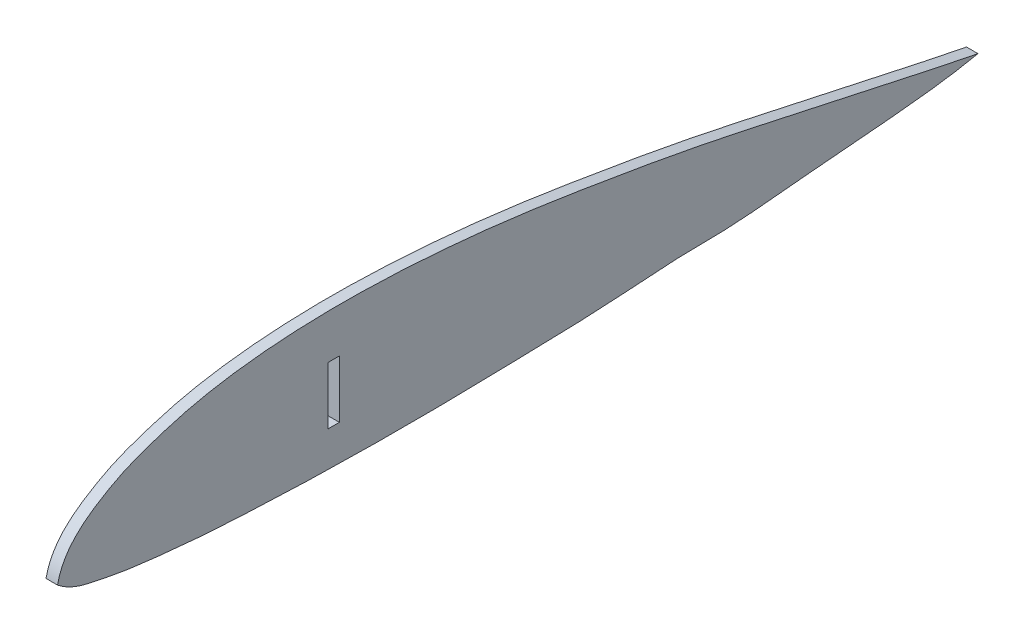
SolidWorks part; units mm, degrees
ref_plane "Спереди" through (0, 0, 0) normal (0, 0, 1) x (1, 0, 0)
ref_plane "Сверху" through (0, 0, 0) normal (0, 1, 0) x (1, 0, 0)
ref_plane "Справа" through (0, 0, 0) normal (1, 0, 0) x (0, 0, -1)
sketch "Эскиз1" plane through (0, 0, 0) normal (1, 0, 0) x (0, 0, -1)
  spline S0 degree 3 poles (-240, 0) (-238.5396, 6.886) (-231.612, 12.3378) (-222.1753, 17.4121) (-214.1119, 20.3435) (-204.1561, 23.2639) (-188.1046, 25.8933) (-168.0072, 26.9601) (-143.9456, 26.0264) (-119.9183, 23.5678) (-95.9538, 19.7588) (-71.9127, 15.562) (-48.006, 10.2206) (-23.9898, 5.1714) (-8.0375, 1.5236) (0, 0) knots 0 0 0 0 0.075346 0.102328 0.12789 0.177564 0.226025 0.321727 0.4173 0.513305 0.60992 0.706974 0.804635 0.902346 1 1 1 1
  spline S1 degree 3 poles (-240, 0) (-236.5239, -2.8866) (-230.2208, -4.0678) (-222.0286, -5.6488) (-214.0096, -6.6085) (-204.0195, -7.6506) (-188.0105, -8.621) (-168.0084, -9.355) (-143.9974, -9.5447) (-119.9964, -9.0006) (-95.9841, -8.4523) (-79.4445, -6.8615) (-63.4129, -6.9414) (-47.4215, -5.1493) (-23.952, -3.3462) (-7.916, -1.6722) (0, 0) knots 0 0 0 0 0.053475 0.078709 0.103753 0.153673 0.203448 0.302856 0.402199 0.501554 0.600955 0.70043 0.70748 0.799996 0.899716 1 1 1 1
  point P0 (-240, 0)
  point P1 (-234, 9.888)
  point P2 (-228, 14.16)
  point P3 (-222, 17.316)
  point P4 (-216, 19.608)
  point P5 (-204, 23.04)
  point P6 (-192, 25.104)
  point P7 (-168, 26.592)
  point P8 (-144, 25.776)
  point P9 (-120, 23.352)
  point P10 (-96, 19.704)
  point P11 (-72, 15.384)
  point P12 (-48, 10.272)
  point P13 (-24, 5.1)
  point P14 (-12, 2.46)
  point P15 (0, 0)
  point P16 (-234, -3.12)
  point P17 (-228, -4.5)
  point P18 (-222, -5.58)
  point P19 (-216, -6.36)
  point P20 (-204, -7.5648)
  point P21 (-192, -8.3472)
  point P22 (-168, -9.24)
  point P23 (-144, -9.4224)
  point P24 (-120, -9)
  point P25 (-96, -8.16)
  point P26 (-72, -6.9024)
  point P27 (-48, -5.34)
  point P28 (-24, -3.24)
  point P29 (-12, -1.98)
extrude "Бобышка-Вытянуть1" add sketch "Эскиз1" along normal blind 3
sketch "Эскиз2" plane through (0, 0, 0) normal (-1, 0, 0) x (0, 0, 1)
  line L13 (169.5, 0) -> (169.5, 15)
  line L14 (169.5, 15) -> (166.5, 15)
  line L15 (166.5, 0) -> (169.5, 0)
  line L16 (166.5, 15) -> (166.5, 0)
extrude "Вырез-Вытянуть1" cut sketch "Эскиз2" against normal blind 3
